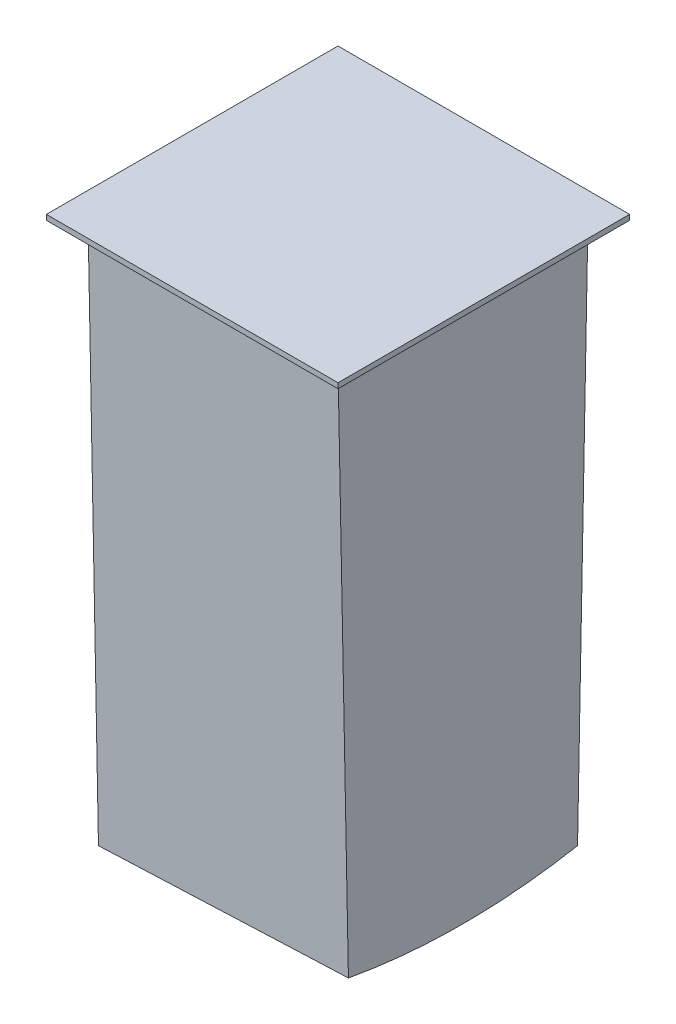
SolidWorks part; units mm, degrees
ref_plane "Front Plane" through (0, 0, 0) normal (0, 0, 1) x (1, 0, 0)
ref_plane "Top Plane" through (0, 0, 0) normal (0, 1, 0) x (1, 0, 0)
ref_plane "Right Plane" through (0, 0, 0) normal (1, 0, 0) x (0, 0, -1)
sketch3d "3DSketch2" plane through (0, 0, 0) normal (0, 0, 1) x (1, 0, 0)
sketch "Tall side" plane through (0, 0, 0) normal (1, 0, 0) x (0, 0, -1)
  line L0 (640.7123, 673.5946) -> (335.9123, 673.5946)
  line L1 (335.9123, 673.5946) -> (348.6123, 6.8446)
  line L2 (348.6123, 6.8446) -> (628.0123, 6.8446) construction
  line L3 (628.0123, 6.8446) -> (640.7123, 673.5946)
  line L4 (488.3123, 673.5946) -> (488.3123, -18.5554) construction
  arc A0 (628.0123, 6.8446) -> (348.6123, 6.8446) centre (488.3123, 378.3196) cw
  point P2 (488.3123, -18.5554)
  point P6 (488.3123, 673.5946)
  dimension "D1" = 25.4
  dimension "D2" = 279.4
  dimension "D3" = 304.8
  dimension "D4" = 692.15
sketch "Short side" plane through (304.8, 0, 0) normal (1, 0, 0) x (0, 0, -1)
  line L0 (640.7163, 673.5946) -> (335.9163, 673.5946)
  line L1 (335.9163, 673.5946) -> (348.6163, 19.5446)
  line L2 (348.6163, 19.5446) -> (628.0163, 19.5446) construction
  line L3 (628.0163, 19.5446) -> (640.7163, 673.5946)
  line L5 (488.3163, 673.5946) -> (488.3163, 6.8446) construction
  arc A0 (628.0163, 19.5446) -> (348.6163, 19.5446) centre (488.3163, 781.5446) cw
  point P6 (488.3163, 673.5946)
  dimension "D1" = 654.05
  dimension "D2" = 279.4
  dimension "D3" = 304.8
  dimension "D4" = 12.7
loft "Body" add profiles "Tall side", "Short side"
sketch "Sketch9" plane through (0, 673.5946, 0) normal (0, 1, 0) x (1, 0, 0)
  line L0 (0, 640.7123) -> (0, 335.9123) construction
  line L1 (-25.4, 666.1143) -> (330.2, 666.1143)
  line L2 (-25.4, 666.1143) -> (-25.4, 310.5143)
  line L3 (-25.4, 310.5143) -> (330.2, 310.5143)
  line L4 (330.2, 666.1143) -> (330.2, 310.5143)
  line L7 (304.8, 640.7163) -> (304.8, 335.9163) construction
  line L8 (0, 335.9123) -> (304.8, 335.9163) construction
  line L9 (0, 640.7123) -> (304.8, 640.7163) construction
  point P10 (152.4, 335.9143)
  point P11 (152.4, 640.7143)
  dimension "D1" = 25.4
  dimension "D2" = 25.4
  dimension "D3" = 25.4
  dimension "D4" = 25.4
extrude "Lid" add sketch "Sketch9" along normal blind 6.35
